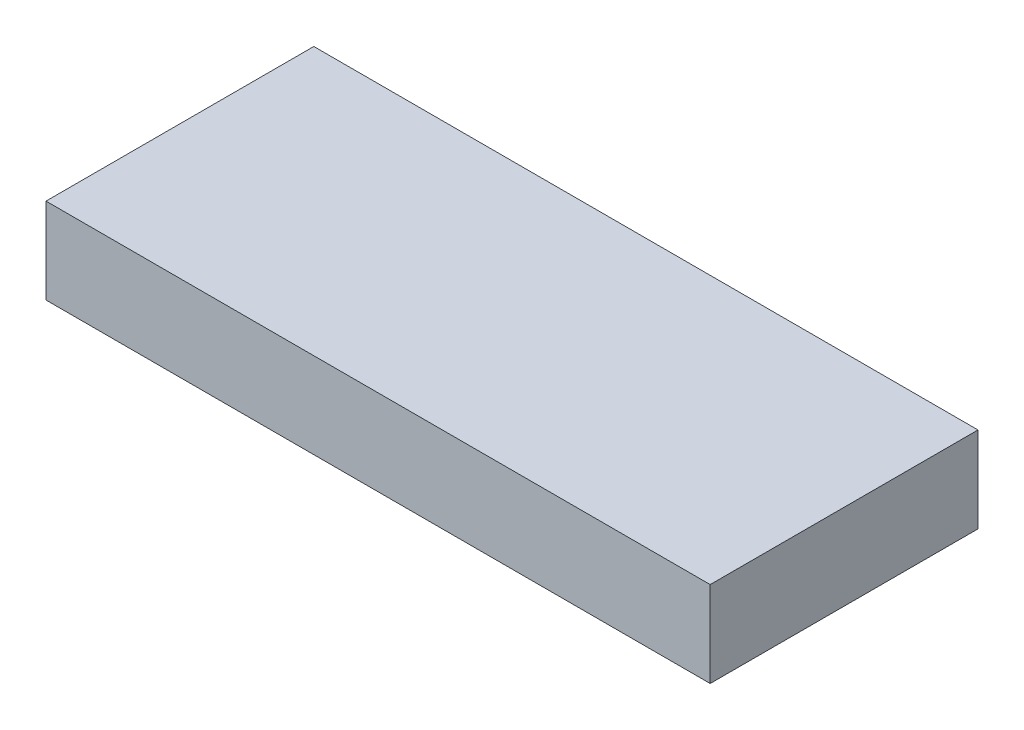
SolidWorks part; units mm, degrees
ref_plane "Front Plane" through (0, 0, 0) normal (0, 0, 1) x (1, 0, 0)
ref_plane "Top Plane" through (0, 0, 0) normal (0, 1, 0) x (1, 0, 0)
ref_plane "Right Plane" through (0, 0, 0) normal (1, 0, 0) x (0, 0, -1)
sketch "Sketch1" plane through (0, 0, 0) normal (0, 1, 0) x (1, 0, 0)
  line L1 (-46.5, -18.75) -> (46.5, -18.75)
  line L2 (-46.5, -18.75) -> (-46.5, 18.75)
  line L3 (-46.5, 18.75) -> (46.5, 18.75)
  line L4 (46.5, -18.75) -> (46.5, 18.75)
  line L5 (-46.5, -18.75) -> (46.5, 18.75) construction
  line L6 (-46.5, 18.75) -> (46.5, -18.75) construction
  point P0 (0, 0)
  dimension "D1" = 93
  dimension "D2" = 37.5
extrude "Boss-Extrude1" add sketch "Sketch1" along normal blind 12
